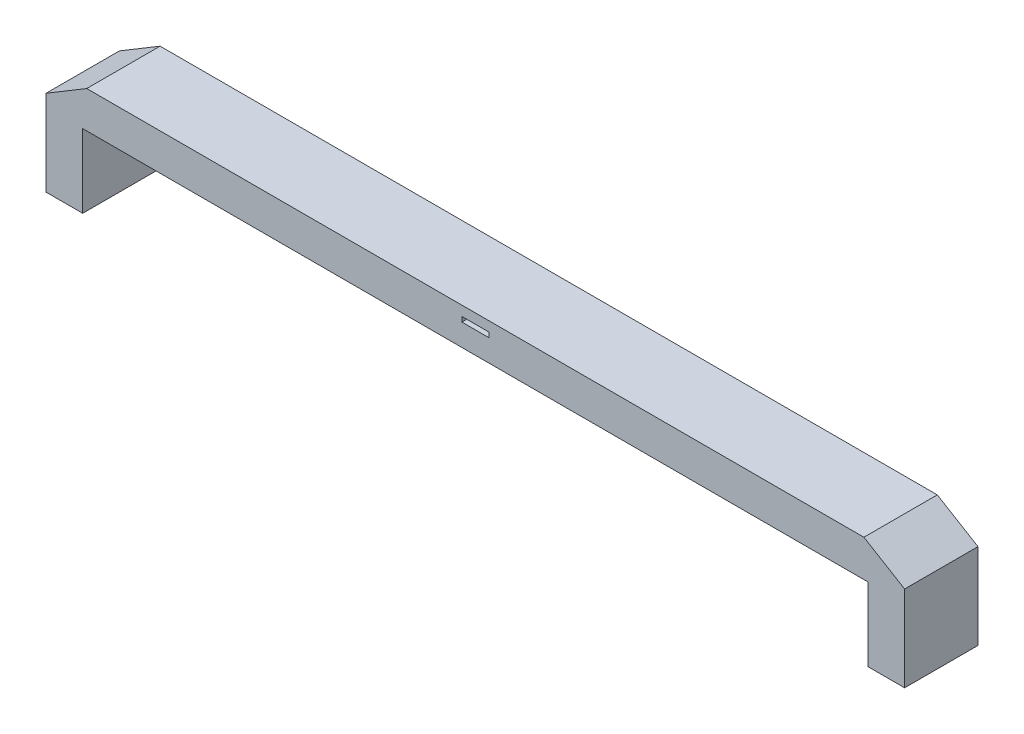
SolidWorks part; units mm, degrees
ref_plane "Front Plane" through (0, 0, 0) normal (0, 0, 1) x (1, 0, 0)
ref_plane "Top Plane" through (0, 0, 0) normal (0, 1, 0) x (1, 0, 0)
ref_plane "Right Plane" through (0, 0, 0) normal (1, 0, 0) x (0, 0, -1)
sketch "Sketch1" plane through (0, 0, 0) normal (0, 1, 0) x (1, 0, 0)
  line L0 (0, 0) -> (-321, 0)
  line L1 (-321, 0) -> (-321, -30)
  line L2 (-321, -30) -> (0, -30)
  line L3 (0, -30) -> (0, 0)
  dimension "D1" = 321
  dimension "D2" = 30
extrude "Boss-Extrude1" add sketch "Sketch1" along normal blind 15
sketch "Sketch2" plane through (0, 15, 0) normal (0, 1, 0) x (1, 0, 0)
  line L0 (-321, 0) -> (-336, 0)
  line L1 (-336, 0) -> (-336, -30)
  line L2 (-336, -30) -> (-321, -30)
  line L3 (-321, -30) -> (-321, 0)
  line L4 (0, 0) -> (0, -30)
  line L5 (0, -30) -> (15, -30)
  line L6 (15, -30) -> (15, 0)
  line L7 (15, 0) -> (0, 0)
  dimension "D1" = 15
  dimension "D2" = 15
extrude "Boss-Extrude2" add sketch "Sketch2" against normal blind 45
sketch "Sketch3" plane through (0, 0, 0) normal (0, -1, 0) x (1, 0, 0)
  line L0 (-180.5, 30) -> (-180.5, 0)
  line L1 (-321, 30) -> (0, 30) construction
  line L2 (0, 0) -> (-321, 0) construction
  line L3 (-180.5, 0) -> (-140.5, 0)
  line L4 (-140.5, 0) -> (-140.5, 30)
  line L5 (-140.5, 30) -> (-180.5, 30)
  line L6 (-321, 0) -> (-321, 30) construction
  point P8 (-180.5, 15)
  dimension "D1" = 40
  dimension "D2" = 140.5
extrude "Boss-Extrude3" add sketch "Sketch3" along normal blind 0.0001
sketch "Sketch4" plane through (0, 0, 30) normal (0, 0, 1) x (1, 0, 0)
  line L1 (-166, 11) -> (-155, 11)
  line L2 (-166, 11) -> (-166, 9)
  line L3 (-166, 9) -> (-155, 9)
  line L4 (-155, 11) -> (-155, 9)
  line L5 (-140.5, -0.0001) -> (-140.5, 0) construction
  line L7 (-336, 15) -> (15, 15) construction
  dimension "D1" = 2
  dimension "D2" = 11
  dimension "D3" = 4
  dimension "D4" = 14.5
extrude "Cut-Extrude1" cut sketch "Sketch4" against normal blind 7.2
chamfer "Chamfer1" distance 10 angle 59 2 edges at (-336, 15, 15) (15, 15, 15)
